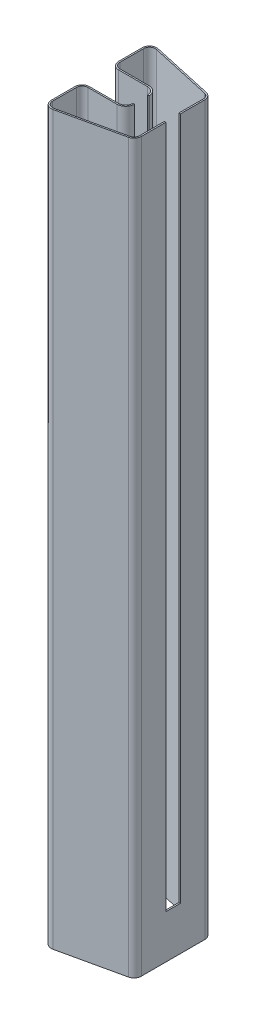
SolidWorks part; units mm, degrees
ref_plane "Front Plane" through (0, 0, 0) normal (0, 0, 1) x (1, 0, 0)
ref_plane "Top Plane" through (0, 0, 0) normal (0, 1, 0) x (1, 0, 0)
ref_plane "Right Plane" through (0, 0, 0) normal (1, 0, 0) x (0, 0, -1)
sketch "Sketch1" plane through (0, 0, 0) normal (0, 1, 0) x (1, 0, 0)
  line L0 (62.4977, -33.3724) -> (51.9977, -31.0446)
  line L1 (51.9977, -31.0446) -> (51.9977, -36.5446)
  line L2 (51.9977, -36.5446) -> (57.9977, -36.5446)
  line L3 (57.9977, -36.5446) -> (57.9977, -40.5446)
  line L4 (57.9977, -40.5446) -> (51.9977, -40.5446)
  line L5 (51.9977, -40.5446) -> (51.9977, -46.0446)
  line L6 (51.9977, -46.0446) -> (62.4977, -43.7168)
  line L7 (62.4977, -43.7168) -> (62.4977, -33.3724)
  point P10 (57.9977, -38.5446)
  point P11 (62.4977, -38.5446)
  dimension "D1" = 90
  dimension "D2" = 90
  dimension "D3" = 90
  dimension "D4" = 90
  dimension "D5" = 77.5
  dimension "D6" = 77.5
  dimension "D7" = 6
  dimension "D8" = 4
  dimension "D9" = 5.5
  dimension "D10" = 5.5
  dimension "D11" = 6
  dimension "D12" = 4.5
  dimension "D13" = 10.3444
extrude "Boss-Extrude1" add sketch "Sketch1" along normal blind 100
fillet "Fillet1" radius 1 8 edges at (57.9977, 50, 40.5446) (51.9977, 50, 46.0446) (51.9977, 50, 40.5446) (57.9977, 50, 36.5446) (51.9977, 50, 36.5446) (51.9977, 50, 31.0446) (62.4977, 50, 33.3724) (62.4977, 50, 43.7168)
shell "Shell3" thickness 0.2
sketch "Sketch2" plane through (0, 100, 0) normal (0, 1, 0) x (1, 0, 0)
  line L1 (57.445, -39.5446) -> (63.4408, -39.5446)
  line L2 (57.445, -39.5446) -> (57.445, -37.5446)
  line L3 (57.445, -37.5446) -> (63.4408, -37.5446)
  line L4 (63.4408, -39.5446) -> (63.4408, -37.5446)
  dimension "D1" = 2
  dimension "D2" = 1
  dimension "D3" = 1
  dimension "D4" = 1
extrude "Cut-Extrude1" cut sketch "Sketch2" against normal blind 94
